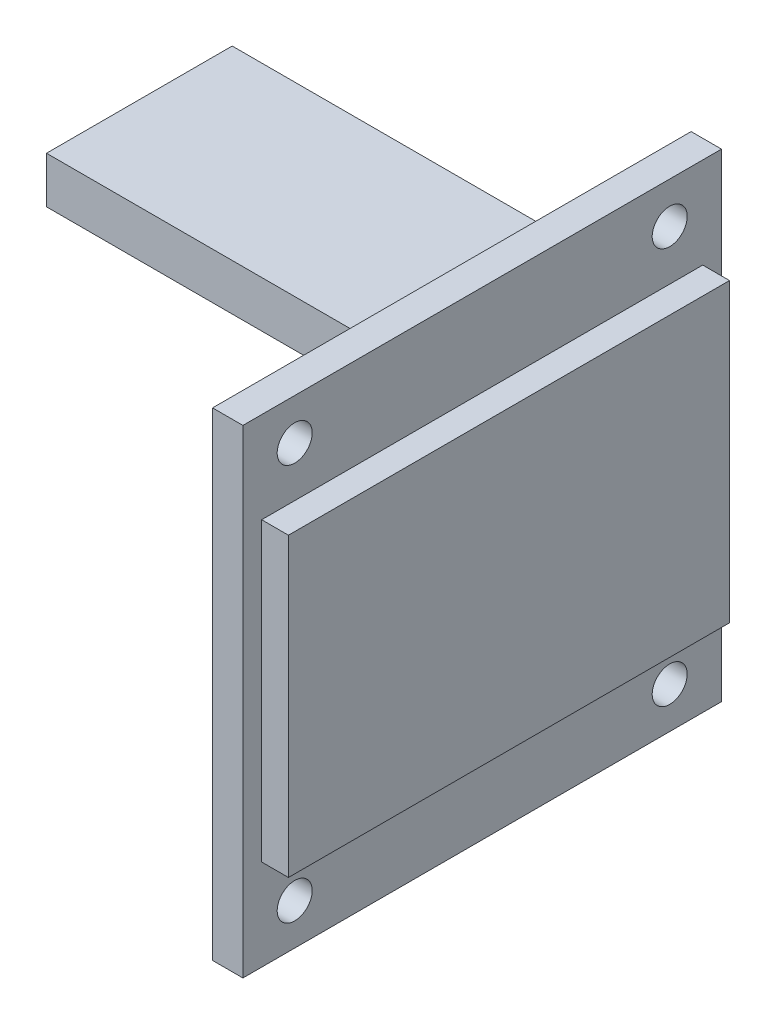
SolidWorks part; units mm, degrees
ref_plane "前视基准面" through (0, 0, 0) normal (0, 0, 1) x (1, 0, 0)
ref_plane "上视基准面" through (0, 0, 0) normal (0, 1, 0) x (1, 0, 0)
ref_plane "右视基准面" through (0, 0, 0) normal (1, 0, 0) x (0, 0, -1)
sketch "草图1" plane through (0, 0, 0) normal (1, 0, 0) x (0, 0, -1)
  line L1 (-13.4, 13.4) -> (13.4, 13.4)
  line L2 (-13.4, 13.4) -> (-13.4, -13.4)
  line L3 (-13.4, -13.4) -> (13.4, -13.4)
  line L4 (13.4, 13.4) -> (13.4, -13.4)
  line L5 (-13.4, 13.4) -> (13.4, -13.4) construction
  line L6 (-13.4, -13.4) -> (13.4, 13.4) construction
  point P0 (0, 0)
  dimension "D1" = 26.8
  dimension "D2" = 26.8
extrude "凸台-拉伸1" add sketch "草图1" along normal blind 3.2
sketch "草图2" plane through (3.2, 0, 0) normal (1, 0, 0) x (0, 0, -1)
  line L1 (-12.35, 8.3) -> (12.35, 8.3)
  line L2 (-12.35, 8.3) -> (-12.35, -8.3)
  line L3 (-12.35, -8.3) -> (12.35, -8.3)
  line L4 (13.4, -13.4) -> (13.4, 13.4)
  line L5 (13.4, 13.4) -> (-13.4, 13.4)
  line L6 (-13.4, 13.4) -> (-13.4, -13.4)
  line L7 (-13.4, -13.4) -> (13.4, -13.4)
  line L8 (13.4, -13.4) -> (13.4, 13.4)
  line L9 (13.4, 13.4) -> (-13.4, 13.4)
  line L10 (-13.4, 13.4) -> (-13.4, -13.4)
  line L11 (-13.4, -13.4) -> (13.4, -13.4)
  line L12 (12.35, 8.3) -> (12.35, -8.3)
  line L13 (-12.35, 8.3) -> (12.35, -8.3) construction
  line L14 (-12.35, -8.3) -> (12.35, 8.3) construction
  point P2 (0, 0)
  dimension "D2" = 24.7
  dimension "D3" = 16.6
  dimension "D1" = 0
extrude "切除-拉伸1" cut sketch "草图2" against normal blind 1.5 contours L8 L9 L10 L11 | L2 L1 L12 L3
sketch "草图3" plane through (0, 0, 0) normal (-1, 0, 0) x (0, 0, 1)
  line L0 (0, 0) -> (0, 13.4) construction
  line L1 (-13.4, 13.4) -> (13.4, 13.4) construction
  line L3 (-5.2, 12.9) -> (5.2, 12.9)
  line L4 (-5.2, 12.9) -> (-5.2, 10.3)
  line L5 (-5.2, 10.3) -> (5.2, 10.3)
  line L6 (5.2, 12.9) -> (5.2, 10.3)
  line L7 (-5.2, 12.9) -> (5.2, 10.3) construction
  line L8 (-5.2, 10.3) -> (5.2, 12.9) construction
  point P5 (0, 11.6)
  dimension "D1" = 10.4
  dimension "D2" = 2.6
  dimension "D3" = 3.1
extrude "凸台-拉伸2" add sketch "草图3" along normal blind 17.5
sketch "草图4" plane through (0, 0, 0) normal (-1, 0, 0) x (0, 0, 1)
  line L0 (0, 0) -> (0, -13.4) construction
  line L1 (13.4, -13.4) -> (-13.4, -13.4) construction
  line L2 (0, 0) -> (0, 13.4) construction
  line L3 (-13.4, 13.4) -> (13.4, 13.4) construction
  line L5 (-11.5, 3.6) -> (11.5, 3.6)
  line L6 (-11.5, 3.6) -> (-11.5, -2.4)
  line L7 (-11.5, -2.4) -> (11.5, -2.4)
  line L8 (11.5, 3.6) -> (11.5, -2.4)
  line L9 (-11.5, 3.6) -> (11.5, -2.4) construction
  line L10 (-11.5, -2.4) -> (11.5, 3.6) construction
  point P5 (0, 0.6)
  dimension "D1" = 17
  dimension "D2" = 6
  dimension "D3" = 23
extrude "凸台-拉伸3" add sketch "草图4" along normal blind 1.5
sketch "草图5" plane through (1.7, 0, 0) normal (1, 0, 0) x (0, 0, -1)
  line L1 (-10.5, 11.1) -> (10.5, 11.1) construction
  line L2 (-10.5, 11.1) -> (-10.5, -11.1) construction
  line L3 (-10.5, -11.1) -> (10.5, -11.1) construction
  line L4 (10.5, 11.1) -> (10.5, -11.1) construction
  line L5 (-10.5, 11.1) -> (10.5, -11.1) construction
  line L6 (-10.5, -11.1) -> (10.5, 11.1) construction
  circle A0 centre (-10.5, 11.1) radius 0.98
  circle A1 centre (10.5, 11.1) radius 0.98
  circle A2 centre (10.5, -11.1) radius 0.98
  circle A3 centre (-10.5, -11.1) radius 0.98
  point P0 (0, 0)
  dimension "D1" = 21
  dimension "D2" = 22.2
extrude "切除-拉伸2" cut sketch "草图5" against normal blind 10
